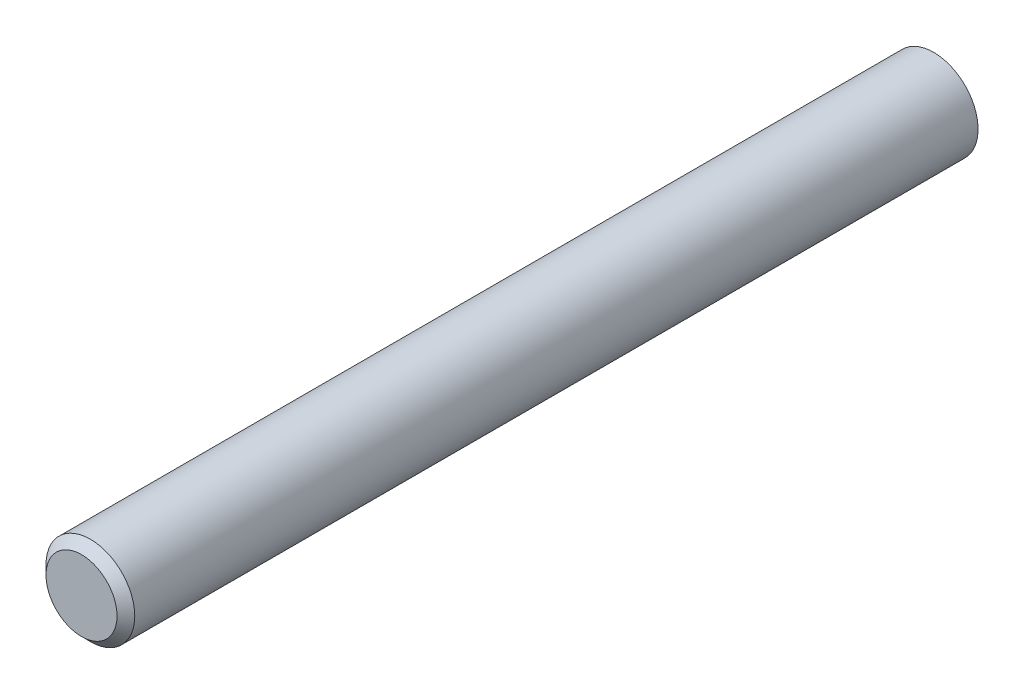
SolidWorks part; units mm, degrees
ref_plane "Front" through (0, 0, 0) normal (0, 0, 1) x (1, 0, 0)
ref_plane "Top" through (0, 0, 0) normal (0, 1, 0) x (1, 0, 0)
ref_plane "Right" through (0, 0, 0) normal (1, 0, 0) x (0, 0, -1)
sketch "Sketch1" plane through (0, 0, 0) normal (0, 0, 1) x (1, 0, 0)
  circle A0 centre (0, 0) radius 3.9688
  dimension "dia" = 7.9375
sketch "Sketch2" plane through (0, 0, 0) normal (1, 0, 0) x (0, 0, -1)
  line L0 (-50.8, 0) -> (50.8, 0) construction
  line L1 (5.2388, 0) -> (-5.2388, 0) construction
  line L3 (50.8, 3.9687) -> (50.8, -3.9688) construction
  line L4 (-50.8, 3.9688) -> (-50.8, -3.9687) construction
  line L5 (-31.75, 3.9688) -> (-31.75, -3.9688) construction
  line L6 (31.75, 3.9688) -> (31.75, -3.9688) construction
  point P6 (0, 0)
  point P10 (50.8, 0)
  point P13 (-50.8, 0)
  point P16 (-31.75, 0)
  point P19 (31.75, 0)
  dimension "D1" = 7.9375
  dimension "lg" = 101.6
  dimension "D2" = 19.05
  dimension "D3" = 19.05
sketch "Sketch3" plane through (0, 0, 0) normal (0, 0, 1) x (1, 0, 0)
  line L0 (0, 3.9688) -> (0, -3.9687) construction
  circle A0 centre (0, 0) radius 3.9688
  dimension "D1" = 7.9375
extrude "Boss-Extrude1" add sketch "Sketch3" along normal mid plane 101.6
chamfer "Chamfer1" distance 0.7937 angle 45 2 edges at (3.9688, 0, -50.8) (3.9688, 0, 50.8)
sketch "Sketch5" plane through (0, 0, -50.8) normal (0, 0, -1) x (-1, 0, 0)
  circle A0 centre (0, 0) radius 3.9688 construction
  circle A1 centre (0, 0) radius 3.9688
extrude "Cut-Extrude2" cut sketch "Sketch5" against normal blind 25.4
equation "\"D1@Sketch2\"=\"dia@sketch1\""
equation "\"D1@Sketch3\"=\"dia@Sketch1\""
equation "\"D1@Boss-Extrude1\"=\"lg@Sketch2\""
equation "\"D1@Chamfer1\"=\"dia@Sketch1\"*.1"
